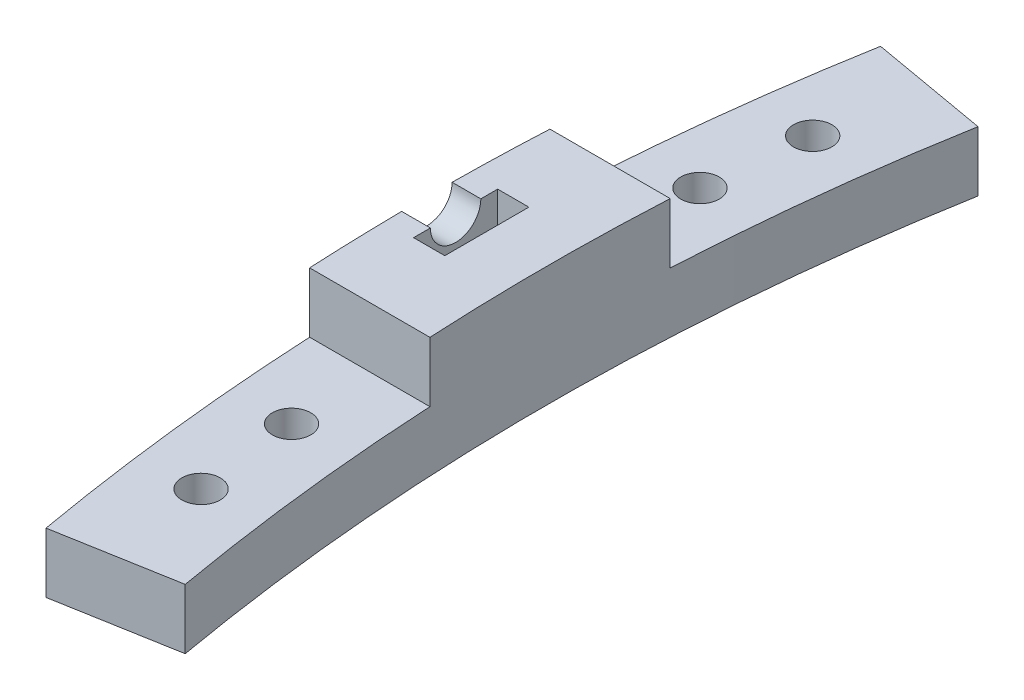
SolidWorks part; units mm, degrees
ref_plane "Front Plane" through (0, 0, 0) normal (0, 0, 1) x (1, 0, 0)
ref_plane "Top Plane" through (0, 0, 0) normal (0, 1, 0) x (1, 0, 0)
ref_plane "Right Plane" through (0, 0, 0) normal (1, 0, 0) x (0, 0, -1)
sketch "Sketch1" plane through (0, 0, 0) normal (0, 1, 0) x (1, 0, 0)
  line L0 (0, 0) -> (-196.9616, -34.7296) construction
  line L1 (0, 0) -> (-196.9616, 34.7296) construction
  line L2 (0, 0) -> (-195, 0) construction
  line L3 (-196.9616, 34.7296) -> (-187.1135, 32.9932)
  line L4 (-187.1135, -32.9932) -> (-196.9616, -34.7296)
  arc A0 (-196.9616, 34.7296) -> (-196.9616, -34.7296) centre (0, 0) ccw
  arc A1 (-187.1135, 32.9932) -> (-187.1135, -32.9932) centre (0, 0) ccw
  arc A2 (-192.0375, -33.8614) -> (-192.0375, 33.8614) centre (0, 0) cw construction
  dimension "D1" = 200
  dimension "D2" = 190
  dimension "D3" = 5
  dimension "D4" = 20
extrude "Boss-Extrude1" add sketch "Sketch1" along normal blind 5
sketch "Sketch2" [suppressed] plane through (0, 7.5, 0) normal (0, 1, 0) x (1, 0, 0)
  line L2 (0, 0) -> (-195, 0) construction
  line L3 (0, 0) -> (-199.4236, -35.1638) construction
  line L4 (0, 0) -> (-199.4236, 35.1638) construction
  line L5 (0, 0) -> (-190, 0) construction
  line L6 (0, 0) -> (-199.4236, -35.1638) construction
  line L7 (0, 0) -> (-199.4236, 35.1638) construction
  line L8 (0, 10) -> (-202.2529, 10) construction
  line L9 (0, 10) -> (0, -10) construction
  line L10 (0, -10) -> (-202.2529, -10) construction
  line L11 (-196.9616, 34.7296) -> (-187.1135, 32.9932)
  line L12 (-196.9616, -34.7296) -> (-187.1135, -32.9932)
  line L13 (-199.7498, -10) -> (-189.7367, -10)
  line L14 (-189.7367, 10) -> (-199.7498, 10)
  arc A0 (-196.9616, 34.7296) -> (-196.9616, -34.7296) centre (0, 0) ccw construction
  arc A1 (-187.1135, 32.9932) -> (-187.1135, -32.9932) centre (0, 0) ccw construction
  arc A2 (-196.9616, 34.7296) -> (-196.9616, -34.7296) centre (0, 0) ccw
  arc A3 (-187.1135, 32.9932) -> (-187.1135, -32.9932) centre (0, 0) ccw
  arc A4 (-199.4236, 35.1638) -> (-199.4236, -35.1638) centre (0, 0) ccw construction
  line M2 (-199.4236, -35.1638) -> (-184.6515, -32.559)
  line M4 (-184.6515, 32.559) -> (-199.4236, 35.1638)
  dimension "D1" = 20
extrude "Cut-Extrude1" [suppressed] cut sketch "Sketch2" against normal blind 1.5 contours A3 A2 L14 M4 | A3 L13 A2 M2
ref_plane "Plane1" through (-195, 0, 0) normal (1, 0, 0) x (0, 0, -1)
sketch "Sketch6" [suppressed] plane through (0, 0, 0) normal (0, -1, 0) x (1, 0, 0)
  line L0 (0, 0) -> (-194.258, 16.9954) construction
  line L1 (0, 0) -> (-195, 0) construction
  line L2 (0, 0) -> (-195, 0) construction
  line L3 (0, 0) -> (-194.258, -16.9954) construction
  arc A0 (-192.0375, 33.8614) -> (-192.0375, -33.8614) centre (0, 0) ccw construction
  dimension "D1" = 5
hole_wizard "Ø3.1 (3.1) Diameter Hole1" [suppressed] positions "Sketch7" profile "Sketch8" hole size "Ø3.1" standard "ISO"
sketch "Sketch7" [suppressed] plane through (0, 0, 0) normal (0, -1, 0) x (-1, 0, 0)
  point P0 (194.258, -16.9954)
  point P3 (194.258, 16.9954)
sketch "Sketch8" plane through (-194.258, 0, 16.9954) normal (1, 0, 0) x (0, 0, -1)
  line L0 (0, 0) -> (0, 7.5)
  line L1 (0, 7.5) -> (1.55, 7.5)
  line L2 (1.55, 7.5) -> (1.55, 0)
  line L5 (1.55, 0) -> (0, 0)
  line L11 (0, -6.35) -> (0, 107.95) construction
  dimension "Thru Hole Dia." = 3.1
  dimension "Thru Hole Depth" = 7.5
sketch "Sketch9" plane through (0, 5, 0) normal (0, 1, 0) x (1, 0, 0)
  line L0 (0, 10) -> (0, -10) construction
  line L1 (0, 0) -> (-200, 0) construction
  line L2 (-199.7498, 10) -> (-189.7367, 10)
  line L3 (-199.7498, -10) -> (-189.7367, -10)
  arc A0 (-196.9616, 34.7296) -> (-196.9616, -34.7296) centre (0, 0) ccw construction
  arc A1 (-187.1135, 32.9932) -> (-187.1135, -32.9932) centre (0, 0) ccw construction
  arc A2 (-189.7367, 10) -> (-189.7367, -10) centre (0, 0) ccw
  arc A3 (-199.7498, 10) -> (-199.7498, -10) centre (0, 0) ccw
  dimension "D1" = 20
extrude "Boss-Extrude2" add sketch "Sketch9" along normal blind 5
ref_plane "Plane2" through (-195, 0, 0) normal (-1, 0, 0) x (0, 0, 1)
sketch "Sketch10" plane through (-195, 0, 0) normal (-1, 0, 0) x (0, 0, 1)
  line L0 (10, 10) -> (-10, 10) construction
  line L1 (3.5, 13.5) -> (-3.5, 13.5)
  line L2 (3.5, 13.5) -> (3.5, 6.5)
  line L3 (3.5, 6.5) -> (-3.5, 6.5)
  line L4 (-3.5, 13.5) -> (-3.5, 6.5)
  line L5 (3.5, 13.5) -> (-3.5, 6.5) construction
  line L6 (3.5, 6.5) -> (-3.5, 13.5) construction
  point P0 (0, 10)
  dimension "D1" = 7
  dimension "D2" = 7
extrude "Cut-Extrude2" cut sketch "Sketch10" along normal blind 2.6
sketch "Sketch11" plane through (-195, 0, 0) normal (-1, 0, 0) x (0, 0, 1)
  line L0 (10, 10) -> (-10, 10) construction
  circle A0 centre (0, 10) radius 2.1
  dimension "D1" = 4.2
extrude "Cut-Extrude3" cut sketch "Sketch11" along normal through all
sketch "Sketch12" plane through (0, 5, 0) normal (0, 1, 0) x (1, 0, 0)
  line L0 (0, 0) -> (-194.258, -16.9954) construction
  line L1 (0, 0) -> (-193.3317, -25.4526) construction
  line L2 (0, 0) -> (-195, 0) construction
  line L3 (0, 0) -> (-195, 0) construction
  line L4 (0, 0) -> (-194.258, 16.9954) construction
  line L5 (0, 0) -> (-193.3317, 25.4526) construction
  arc A0 (-192.0375, 33.8614) -> (-192.0375, -33.8614) centre (0, 0) ccw construction
  dimension "D1" = 10
  dimension "D2" = 15
hole_wizard "Ø3.2 (3.2) Diameter Hole1" positions "Sketch13" profile "Sketch14" hole size "Ø3.2" standard "ISO" end condition through all
sketch "Sketch13" plane through (0, 5, 0) normal (0, 1, 0) x (1, 0, 0)
  point P0 (-194.258, 16.9954)
  point P3 (-193.3317, 25.4526)
  point P6 (-194.258, -16.9954)
  point P9 (-193.3317, -25.4526)
sketch "Sketch14" plane through (-194.258, 5, -16.9954) normal (1, 0, 0) x (0, 0, 1)
  line L0 (0, 0) -> (0, 5)
  line L1 (0, 5) -> (1.6, 5)
  line L2 (1.6, 5) -> (1.6, 0)
  line L5 (1.6, 0) -> (0, 0)
  line L11 (0, -6.35) -> (0, 107.95) construction
  dimension "Thru Hole Dia." = 3.2
  dimension "Thru Hole Depth" = 5
